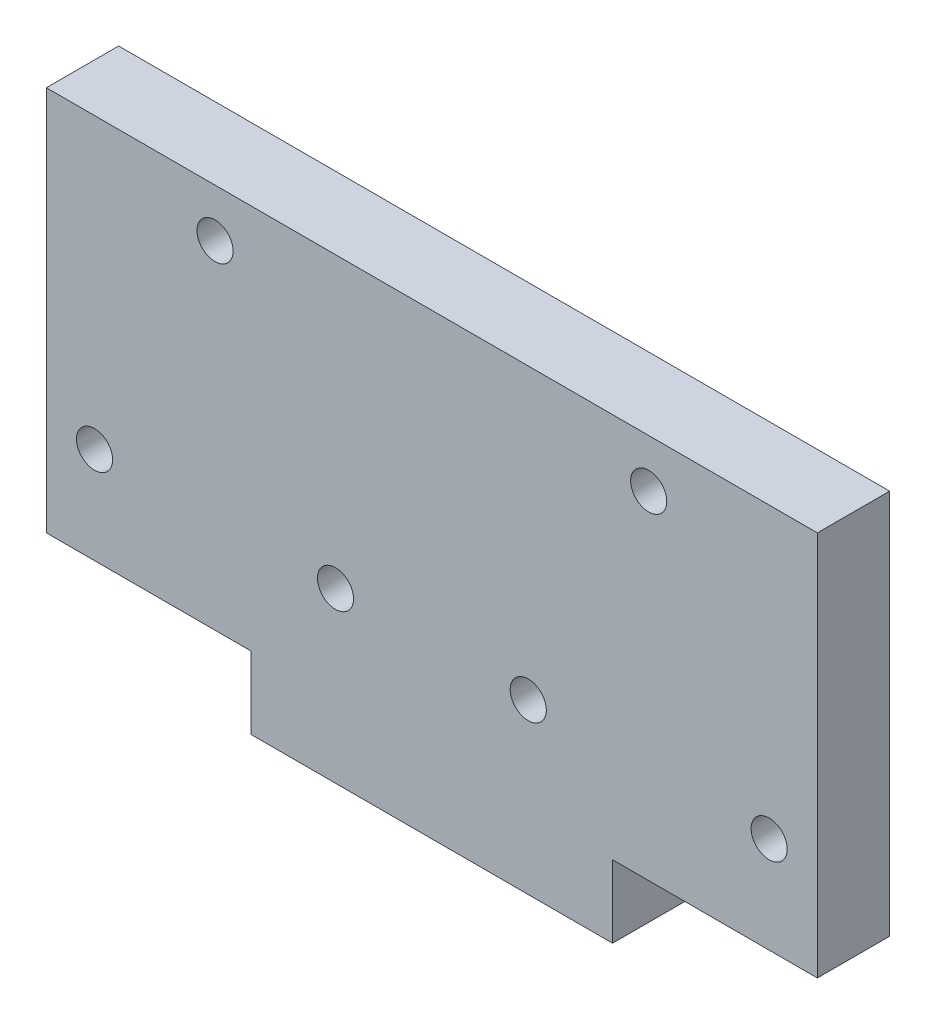
SolidWorks part; units mm, degrees
ref_plane "Plan de face" through (0, 0, 0) normal (0, 0, 1) x (1, 0, 0)
ref_plane "Plan de dessus" through (0, 0, 0) normal (0, 1, 0) x (1, 0, 0)
ref_plane "Plan de droite" through (0, 0, 0) normal (1, 0, 0) x (0, 0, -1)
sketch "Esquisse1" plane through (0, 0, 0) normal (0, 0, 1) x (1, 0, 0)
  line L0 (0, -32) -> (-17, -32)
  line L1 (0, 0) -> (-64, 0)
  line L2 (0, 0) -> (0, -32)
  line L4 (-64, 0) -> (-64, -32)
  line L5 (-17, -32) -> (-17, -38)
  line L6 (-17, -38) -> (-47, -38)
  line L7 (-47, -38) -> (-47, -32)
  line L8 (-47, -32) -> (-64, -32)
  line L9 (-32, 0) -> (-32, -68.9303) construction
  dimension "D1" = 64
  dimension "D2" = 6
  dimension "D3" = 6
  dimension "D4" = 17
  dimension "D5" = 38
  dimension "D6" = 30
extrude "Boss.-Extru.1" add sketch "Esquisse1" along normal blind 6
sketch "Esquisse2" plane through (0, 0, 0) normal (0, 0, -1) x (-1, 0, 0)
  line L0 (32, 0) -> (32, -38) construction
  line L1 (0, 0) -> (64, 0) construction
  line L2 (47, -38) -> (17, -38) construction
  line L3 (28, 0) -> (28, -38) construction
  line L4 (0, -32) -> (0, 0) construction
  line L6 (0, -28) -> (64, -28) construction
  line L7 (36, 0) -> (36, -38) construction
  line L8 (64, 0) -> (64, -32) construction
  circle A0 centre (14, -4) radius 1.5
  circle A1 centre (4, -24) radius 1.5
  circle A2 centre (24, -24) radius 1.5
  circle A3 centre (40, -24) radius 1.5
  circle A4 centre (60, -24) radius 1.5
  circle A5 centre (50, -4) radius 1.5
  dimension "D3" = 14
  dimension "D4" = 3
  dimension "D7" = 3
  dimension "D8" = 4
  dimension "D9" = 4
  dimension "D5" = 3
  dimension "D6" = 28
  dimension "D10" = 4
  dimension "D11" = 4
  dimension "D1" = 4
  dimension "D2" = 28
extrude "Enlèv. mat.-Extru.1" cut sketch "Esquisse2" against normal through all
sketch "Esquisse3" plane through (0, 0, 0) normal (0, 0, -1) x (-1, 0, 0)
  circle A0 centre (14, -4) radius 3
  circle A1 centre (4, -24) radius 3
  circle A2 centre (24, -24) radius 3
  circle A3 centre (40, -24) radius 3
  circle A4 centre (60, -24) radius 3
  circle A5 centre (50, -4) radius 3
  dimension "D1" = 6
  dimension "D2" = 6
  dimension "D3" = 6
  dimension "D4" = 6
  dimension "D5" = 6
  dimension "D6" = 6
extrude "Enlèv. mat.-Extru.2" cut sketch "Esquisse3" against normal blind 3
